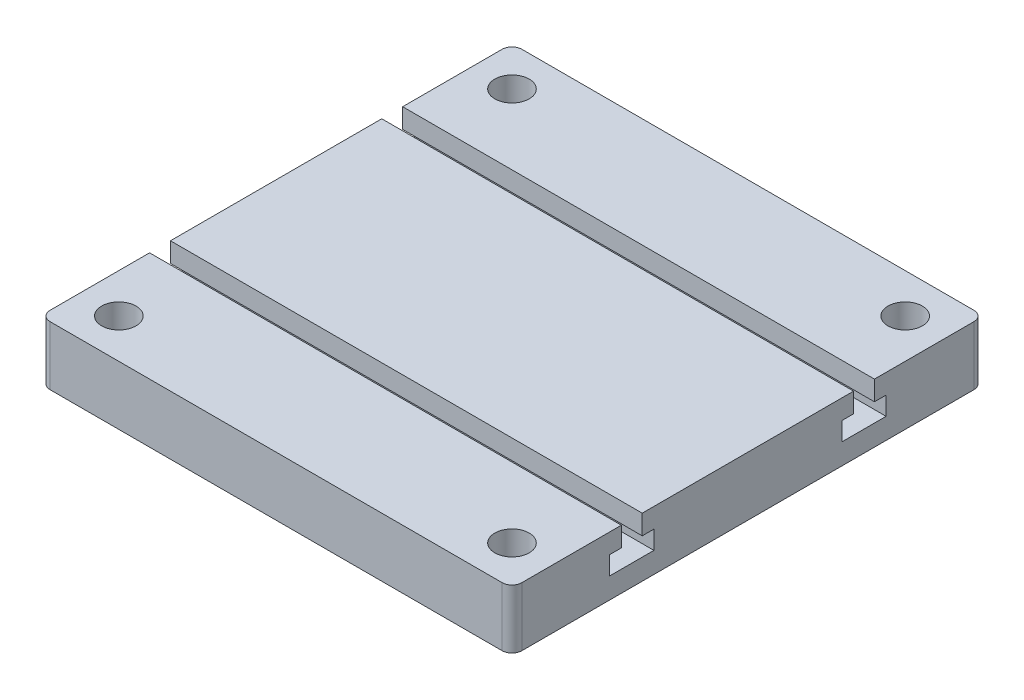
SolidWorks part; units mm, degrees
material "Delrin 2700 NC010, Low Viscosity Acetal Copolymer (SS)"
ref_plane "Front" through (0, 0, 0) normal (0, 0, 1) x (1, 0, 0)
ref_plane "Top" through (0, 0, 0) normal (0, 1, 0) x (1, 0, 0)
ref_plane "Right" through (0, 0, 0) normal (1, 0, 0) x (0, 0, -1)
sketch "Sketch1" plane through (0, 0, 0) normal (0, 1, 0) x (1, 0, 0)
  line L1 (-76.2, 76.2) -> (76.2, 76.2)
  line L2 (-76.2, 76.2) -> (-76.2, -76.2)
  line L3 (-76.2, -76.2) -> (76.2, -76.2)
  line L4 (76.2, 76.2) -> (76.2, -76.2)
  line L5 (-76.2, 76.2) -> (76.2, -76.2) construction
  line L6 (-76.2, -76.2) -> (76.2, 76.2) construction
  point P0 (0, 0)
  dimension "D1" = 152.4
  dimension "D2" = 152.4
extrude "Boss-Extrude1" add sketch "Sketch1" along normal blind 19.05
hole_wizard "CBORE for 1/4 Socket Head Cap Screw1" positions "Sketch2" profile "Sketch3" counterbore size "1/4" standard "ANSI Inch" end condition through all
sketch "Sketch2" plane through (0, 19.05, 0) normal (0, 1, 0) x (1, 0, 0)
  line L1 (-63.5, 63.5) -> (63.5, 63.5) construction
  line L2 (-63.5, 63.5) -> (-63.5, -63.5) construction
  line L3 (-63.5, -63.5) -> (63.5, -63.5) construction
  line L4 (63.5, 63.5) -> (63.5, -63.5) construction
  line L5 (-63.5, 63.5) -> (63.5, -63.5) construction
  line L6 (-63.5, -63.5) -> (63.5, 63.5) construction
  point P0 (-63.5, 63.5)
  point P2 (63.5, 63.5)
  point P4 (63.5, -63.5)
  point P6 (-63.5, -63.5)
  point P108 (0, 0)
  dimension "D1" = 127
  dimension "D2" = 127
sketch "Sketch3" plane through (-63.5, 19.05, -63.5) normal (1, 0, 0) x (0, 0, 1)
  line L0 (0, 0) -> (0, 19.05)
  line L1 (0, 19.05) -> (3.2639, 19.05)
  line L3 (3.2639, 19.05) -> (3.2639, 8.89)
  line L4 (3.2639, 8.89) -> (5.5562, 8.89)
  line L5 (5.5562, 8.89) -> (5.5562, 0)
  line L7 (5.5562, 0) -> (0, 0)
  line L11 (0, -6.35) -> (0, 107.95) construction
  dimension "Thru Hole Dia." = 6.5278
  dimension "Thru Hole Depth" = 19.05
  dimension "C'Bore Dia." = 11.1125
  dimension "C'Bore Depth" = 8.89
sketch "Sketch4" plane through (-76.2, 0, 0) normal (1, 0, 0) x (0, 0, -1)
  line L0 (-40.8765, 19.05) -> (-40.8765, 12.7)
  line L2 (-40.8765, 12.7) -> (-44.6468, 12.7)
  line L3 (-44.6468, 12.7) -> (-44.6468, 6.7469)
  line L4 (-44.6468, 6.7469) -> (-30.3593, 6.7469)
  line L5 (-30.3593, 6.7469) -> (-30.3593, 12.7)
  line L6 (-30.3593, 12.7) -> (-34.1297, 12.7)
  line L7 (-34.1297, 12.7) -> (-34.1297, 19.05)
  line L8 (0, 0) -> (0, 19.05) construction
  line L9 (-37.5031, 6.7469) -> (-37.5031, 19.05) construction
  line L10 (37.5031, 6.7469) -> (37.5031, 19.05) construction
  line L11 (34.1297, 12.7) -> (34.1297, 19.05)
  line L12 (30.3593, 12.7) -> (34.1297, 12.7)
  line L13 (30.3593, 6.7469) -> (30.3593, 12.7)
  line L14 (44.6469, 6.7469) -> (30.3593, 6.7469)
  line L15 (44.6468, 12.7) -> (44.6469, 6.7469)
  line L16 (40.8765, 12.7) -> (44.6468, 12.7)
  line L17 (40.8765, 19.05) -> (40.8765, 12.7)
  line L18 (-40.8765, 19.05) -> (-34.1297, 19.05)
  line L19 (34.1297, 19.05) -> (40.8765, 19.05)
  line L21 (-76.2, 0) -> (76.2, 0) construction
  line L22 (-76.2, 19.05) -> (76.2, 19.05) construction
  dimension "D1" = 14.2875
  dimension "D2" = 6.7469
  dimension "D3" = 6.35
  dimension "D4" = 75.0062
  dimension "D5" = 5.9531
  dimension "D6" = 6.7469
extrude "T-SLOT CUT WITH MCMASTER 8789A16 BIT" cut sketch "Sketch4" along normal through all
fillet "Fillet1" radius 3.175 4 edges at (-76.2, 9.525, 76.2) (76.2, 9.525, 76.2) (76.2, 9.525, -76.2) (-76.2, 9.525, -76.2)
hole_wizard "CBORE for #10 Button Head Cap Screw1" positions "Sketch5" profile "Sketch6" counterbore size "#10" standard "ANSI Inch"
sketch "Sketch5" plane through (0, 0, 0) normal (0, -1, 0) x (-1, 0, 0)
  line L1 (37.5, -37.5) -> (-37.5, -37.5) construction
  line L2 (37.5, -37.5) -> (37.5, 37.5) construction
  line L3 (37.5, 37.5) -> (-37.5, 37.5) construction
  line L4 (-37.5, -37.5) -> (-37.5, 37.5) construction
  line L5 (37.5, -37.5) -> (-37.5, 37.5) construction
  line L6 (37.5, 37.5) -> (-37.5, -37.5) construction
  point P0 (37.5, -37.5)
  point P2 (-37.5, -37.5)
  point P4 (37.5, 37.5)
  point P6 (-37.5, 37.5)
  dimension "D1" = 75
  dimension "D2" = 75
sketch "Sketch6" plane through (-37.5, 0, 37.5) normal (1, 0, 0) x (0, 0, -1)
  line L0 (0, 0) -> (0, 19.05)
  line L1 (0, 19.05) -> (2.921, 19.05)
  line L3 (2.921, 19.05) -> (2.921, 7.874)
  line L4 (2.921, 7.874) -> (5.2705, 7.874)
  line L5 (5.2705, 7.874) -> (5.2705, 0)
  line L7 (5.2705, 0) -> (0, 0)
  line L11 (0, -6.35) -> (0, 107.95) construction
  dimension "Thru Hole Dia." = 5.842
  dimension "Thru Hole Depth" = 19.05
  dimension "C'Bore Dia." = 10.541
  dimension "C'Bore Depth" = 7.874
